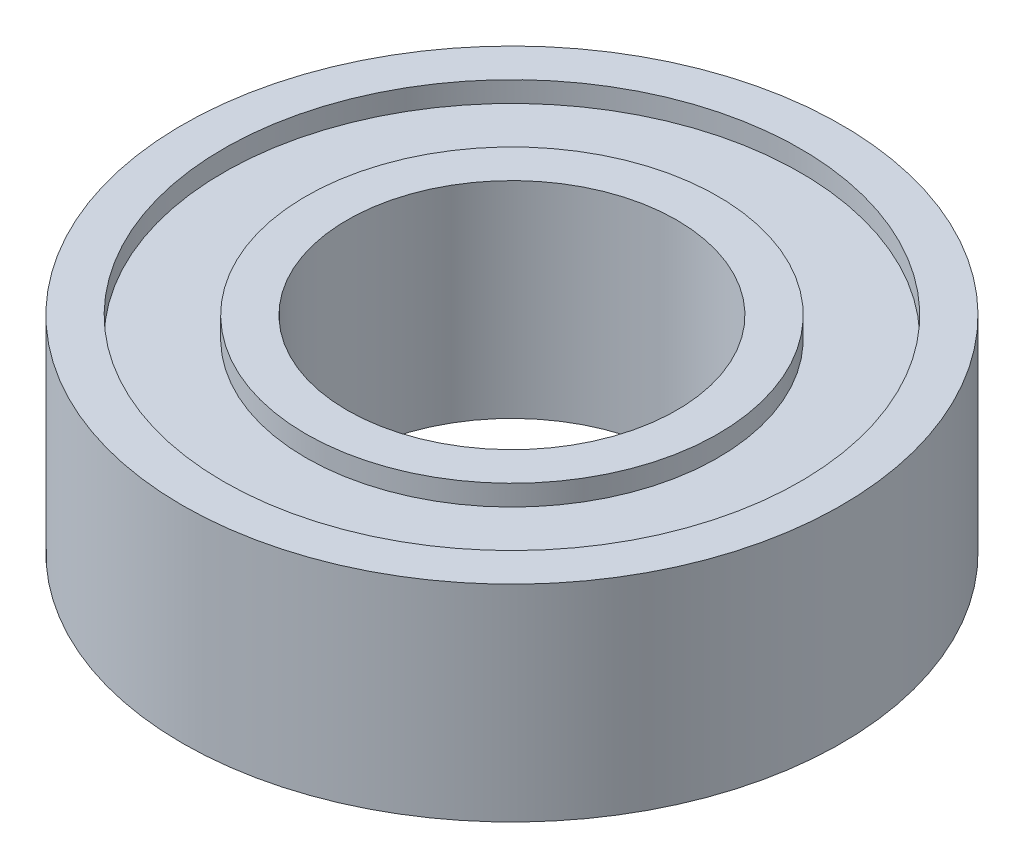
SolidWorks part; units mm, degrees
ref_plane "Front Plane" through (0, 0, 0) normal (0, 0, 1) x (1, 0, 0)
ref_plane "Top Plane" through (0, 0, 0) normal (0, 1, 0) x (1, 0, 0)
ref_plane "Right Plane" through (0, 0, 0) normal (1, 0, 0) x (0, 0, -1)
sketch "Sketch1" plane through (0, 0, 0) normal (0, 1, 0) x (1, 0, 0)
  circle A0 centre (0, 0) radius 4
  circle A1 centre (0, 0) radius 8
  dimension "D1" = 8
  dimension "D2" = 16
extrude "Boss-Extrude1" add sketch "Sketch1" along normal mid plane 5
sketch "Sketch2" plane through (0, 2.5, 0) normal (0, 1, 0) x (1, 0, 0)
  circle A5 centre (0, 0) radius 5
  circle A6 centre (0, 0) radius 5
  circle A8 centre (0, 0) radius 7
  circle A9 centre (0, 0) radius 7
  dimension "D1" = 1
  dimension "D2" = 1
extrude "Cut-Extrude1" cut sketch "Sketch2" against normal blind 0.5
mirror "Mirror1" about plane through (0, 0, 0) normal (0, 1, 0) of "Cut-Extrude1"
